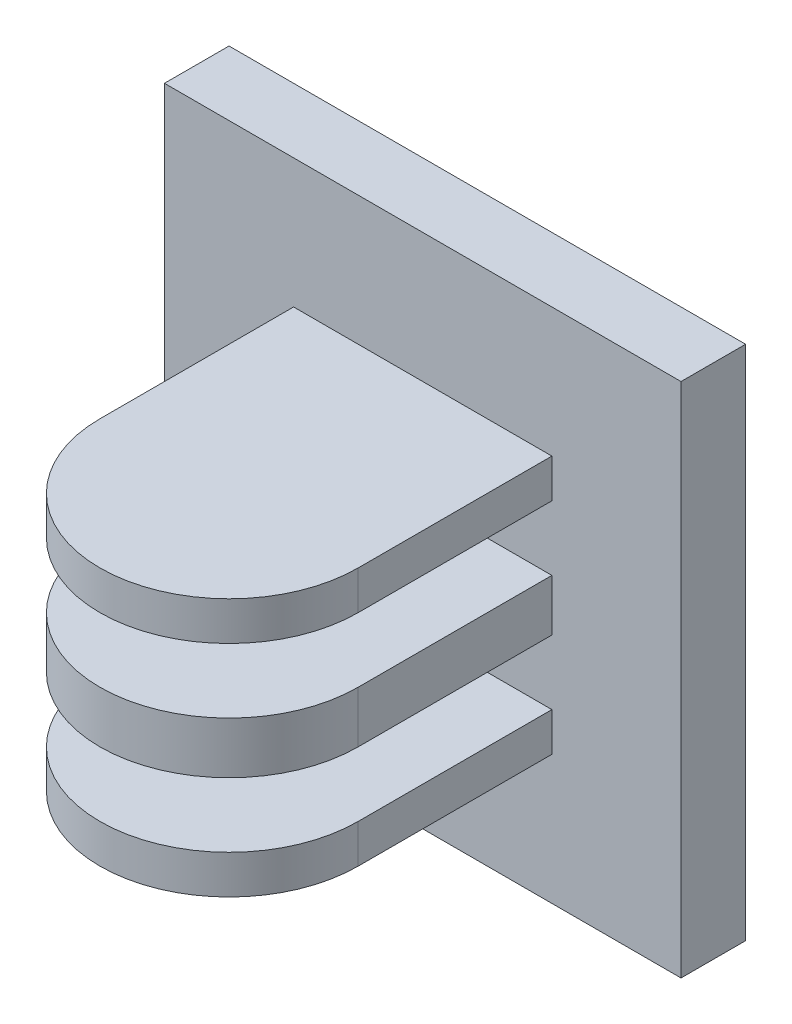
SolidWorks part; units mm, degrees
ref_plane "Front Plane" through (0, 0, 0) normal (0, 0, 1) x (1, 0, 0)
ref_plane "Top Plane" through (0, 0, 0) normal (0, 1, 0) x (1, 0, 0)
ref_plane "Right Plane" through (0, 0, 0) normal (1, 0, 0) x (0, 0, -1)
sketch "Sketch1" plane through (0, 0, 0) normal (0, 0, 1) x (1, 0, 0)
  line L1 (-20, 20) -> (20, 20)
  line L2 (-20, 20) -> (-20, -20)
  line L3 (-20, -20) -> (20, -20)
  line L4 (20, 20) -> (20, -20)
  point P4 (0, 20)
  point P6 (-20, 0)
  dimension "D1" = 40
  dimension "D2" = 40
extrude "Boss-Extrude1" add sketch "Sketch1" along normal blind 5
sketch "Sketch2" plane through (0, 0, 0) normal (0, 1, 0) x (1, 0, 0)
  line L0 (-20, -5) -> (20, -5) construction
  line L1 (10, -5) -> (-10, -5)
  line L2 (10, -5) -> (10, -20)
  line L4 (-10, -5) -> (-10, -20)
  arc A0 (-10, -20) -> (10, -20) centre (0, -20) ccw
  point P7 (0, -5)
  point P11 (0, 0)
  dimension "D2" = 15
  dimension "D1" = 20
extrude "Boss-Extrude2" add sketch "Sketch2" against normal blind 20 from offset 10
sketch "Sketch3" plane through (0, 10, 0) normal (0, 1, 0) x (1, 0, 0)
  line L0 (10, -20) -> (10, -5)
  line L1 (10, -5) -> (-10, -5)
  line L2 (-10, -5) -> (-10, -20)
  arc A0 (10, -20) -> (-10, -20) centre (0, -20) cw
extrude "Cut-Extrude1" cut sketch "Sketch3" against normal blind 5 from offset 3 offset against normal yes
sketch "Sketch4" plane through (0, 10, 0) normal (0, 1, 0) x (1, 0, 0)
  line L0 (-10, -5) -> (-10, -20) construction
  line L1 (10, -20) -> (10, -5)
  line L2 (10, -5) -> (-10, -5)
  line L3 (-10, -5) -> (-10, -20)
  arc A0 (10, -20) -> (-10, -20) centre (0, -20) cw
  arc A1 (-10, -20) -> (10, -20) centre (0, -20) ccw construction
extrude "Cut-Extrude2" cut sketch "Sketch4" against normal blind 5 from offset 12 offset against normal yes
